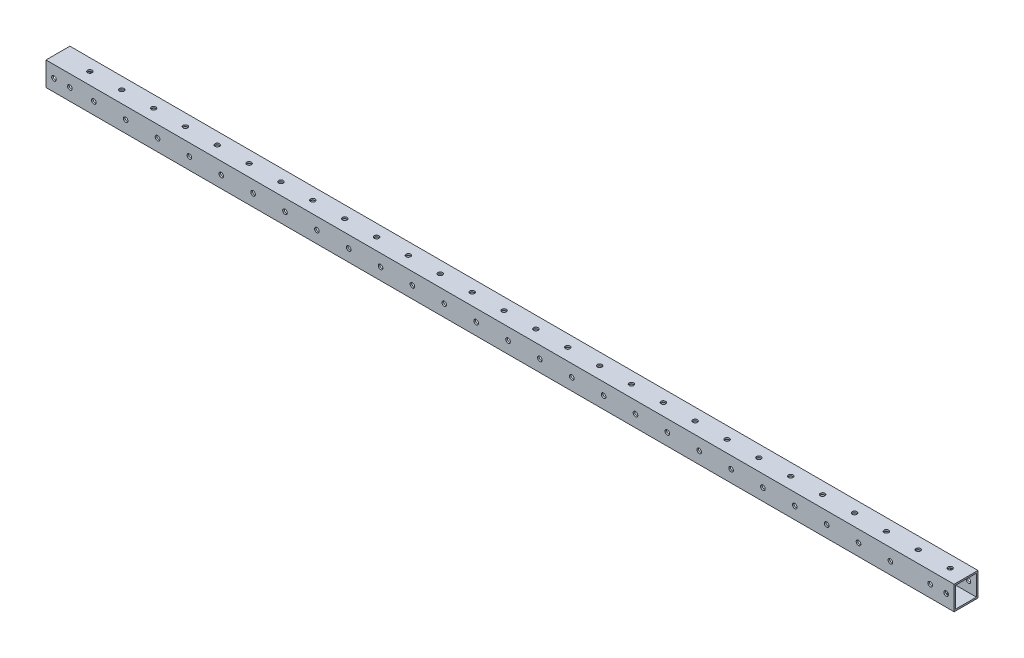
SolidWorks part; units mm, degrees
material "Thornel Mat VMA"
ref_plane "前视基准面" through (0, 0, 0) normal (0, 0, 1) x (1, 0, 0)
ref_plane "上视基准面" through (0, 0, 0) normal (0, 1, 0) x (1, 0, 0)
ref_plane "右视基准面" through (0, 0, 0) normal (1, 0, 0) x (0, 0, -1)
other "Configuration Table"
sketch "草图1" plane through (0, 0, 0) normal (1, 0, 0) x (0, 0, -1)
  line L0 (-6.5, -6.5) -> (-6.5, 6.5)
  line L1 (-7.5, -7.5) -> (7.5, -7.5)
  line L2 (-7.5, -7.5) -> (-7.5, 7.5)
  line L3 (-7.5, 7.5) -> (7.5, 7.5)
  line L4 (7.5, -7.5) -> (7.5, 7.5)
  line L5 (-7.5, -7.5) -> (7.5, 7.5) construction
  line L6 (-7.5, 7.5) -> (7.5, -7.5) construction
  line L7 (-6.5, 6.5) -> (6.5, 6.5)
  line L8 (6.5, -6.5) -> (6.5, 6.5)
  line L9 (-6.5, -6.5) -> (6.5, -6.5)
  point P0 (0, 0)
  dimension "D1" = 15
  dimension "D2" = 15
  dimension "D3" = 1
extrude "凸台-拉伸1" add sketch "草图1" along normal blind 570
sketch "草图2" plane through (0, 7.5, 0) normal (0, 1, 0) x (1, 0, 0)
  line L0 (-15.1019, 0) -> (579.4485, 0) construction
  line L1 (0, 7.5) -> (0, -7.5) construction
  circle A0 centre (20, 0) radius 1.45
  circle A1 centre (40, 0) radius 1.45
  circle A2 centre (60, 0) radius 1.45
  circle A3 centre (80, 0) radius 1.45
  circle A4 centre (100, 0) radius 1.45
  circle A5 centre (120, 0) radius 1.45
  circle A6 centre (140, 0) radius 1.45
  circle A7 centre (160, 0) radius 1.45
  circle A8 centre (180, 0) radius 1.45
  circle A9 centre (200, 0) radius 1.45
  circle A10 centre (220, 0) radius 1.45
  circle A11 centre (240, 0) radius 1.45
  circle A12 centre (260, 0) radius 1.45
  circle A13 centre (280, 0) radius 1.45
  circle A14 centre (300, 0) radius 1.45
  circle A15 centre (320, 0) radius 1.45
  circle A16 centre (340, 0) radius 1.45
  circle A17 centre (360, 0) radius 1.45
  circle A18 centre (380, 0) radius 1.45
  circle A19 centre (400, 0) radius 1.45
  circle A20 centre (420, 0) radius 1.45
  circle A21 centre (440, 0) radius 1.45
  circle A22 centre (460, 0) radius 1.45
  circle A23 centre (480, 0) radius 1.45
  circle A24 centre (500, 0) radius 1.45
  circle A25 centre (520, 0) radius 1.45
  circle A26 centre (540, 0) radius 1.45
  circle A27 centre (560, 0) radius 1.45
  dimension "D1" = 2.9
  dimension "D2" = 20
  dimension "D3" = 28
extrude "切除-拉伸1" cut sketch "草图2" against normal through all
sketch "草图3" plane through (0, 0, 7.5) normal (0, 0, 1) x (1, 0, 0)
  line L0 (-7.5852, 0) -> (594.7728, 0) construction
  line L1 (0, 7.5) -> (0, -7.5) construction
  line L2 (570, 7.5) -> (570, -7.5) construction
  circle A0 centre (5, 0) radius 1.45
  circle A1 centre (15, 0) radius 1.45
  circle A2 centre (565, 0) radius 1.45
  circle A3 centre (555, 0) radius 1.45
  circle A4 centre (30, 0) radius 1.45
  circle A5 centre (50, 0) radius 1.45
  circle A6 centre (70, 0) radius 1.45
  circle A7 centre (90, 0) radius 1.45
  circle A8 centre (110, 0) radius 1.45
  circle A9 centre (130, 0) radius 1.45
  circle A10 centre (150, 0) radius 1.45
  circle A11 centre (170, 0) radius 1.45
  circle A12 centre (190, 0) radius 1.45
  circle A13 centre (210, 0) radius 1.45
  circle A14 centre (230, 0) radius 1.45
  circle A15 centre (250, 0) radius 1.45
  circle A16 centre (270, 0) radius 1.45
  circle A17 centre (290, 0) radius 1.45
  circle A18 centre (310, 0) radius 1.45
  circle A19 centre (330, 0) radius 1.45
  circle A20 centre (350, 0) radius 1.45
  circle A21 centre (370, 0) radius 1.45
  circle A22 centre (390, 0) radius 1.45
  circle A23 centre (410, 0) radius 1.45
  circle A24 centre (430, 0) radius 1.45
  circle A25 centre (450, 0) radius 1.45
  circle A26 centre (470, 0) radius 1.45
  circle A27 centre (490, 0) radius 1.45
  circle A28 centre (510, 0) radius 1.45
  circle A29 centre (530, 0) radius 1.45
  dimension "D1" = 2.9
  dimension "D3" = 10
  dimension "D4" = 5
  dimension "D5" = 10
  dimension "D6" = 2.9
  dimension "D7" = 30
  dimension "D8" = 2.9
  dimension "D2" = 5
  dimension "D9" = 26
extrude "切除-拉伸2" cut sketch "草图3" against normal through all
